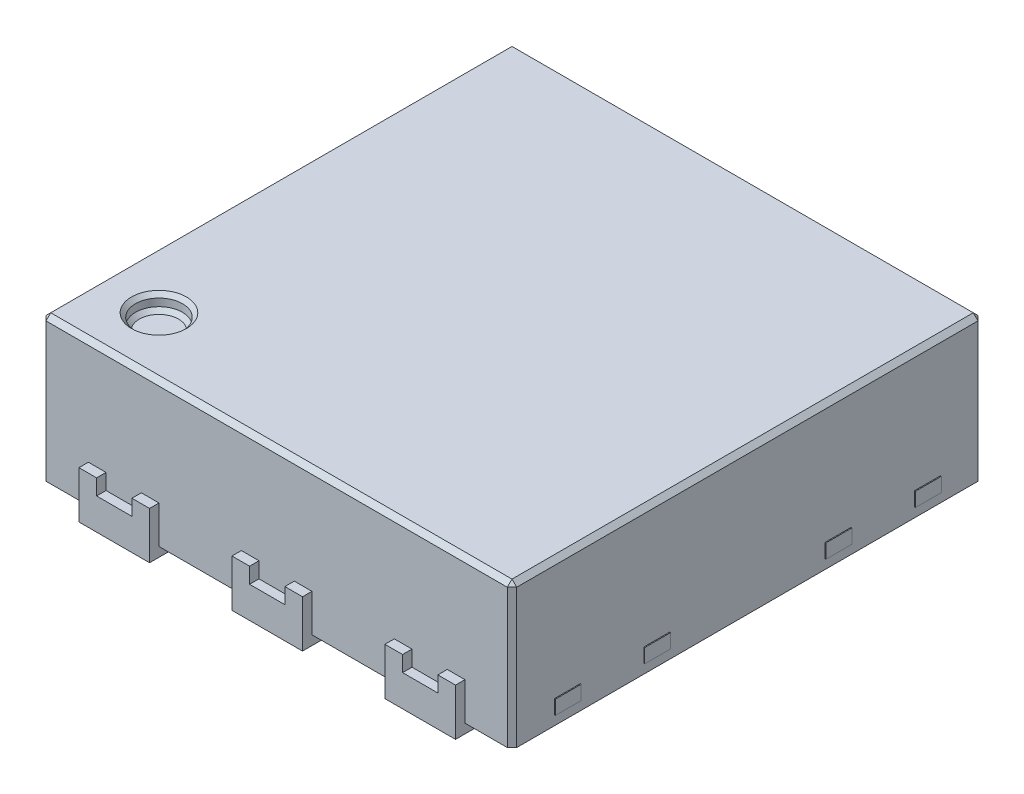
SolidWorks part; units mm, degrees
ref_plane "Front Plane" through (0, 0, 0) normal (0, 0, 1) x (1, 0, 0)
ref_plane "Top Plane" through (0, 0, 0) normal (0, 1, 0) x (1, 0, 0)
ref_plane "Right Plane" through (0, 0, 0) normal (1, 0, 0) x (0, 0, -1)
sketch "Sketch1" plane through (0, 0, 0) normal (0, 1, 0) x (1, 0, 0)
  line L0 (0, 0) -> (-0.49, 0) construction
  line L1 (0, 0) -> (0.49, 0) construction
  line L2 (0, 0) -> (0, 0.895) construction
  line L3 (-0.825, 0.5) -> (-0.155, 0.5)
  line L4 (-0.825, -0.5) -> (-0.825, -0.3325) construction
  line L6 (-0.155, 0.5) -> (-0.155, -0.5)
  line L7 (-0.825, 0.5) -> (-0.155, -0.5) construction
  line L8 (-0.825, -0.5) -> (-0.155, 0.5) construction
  line L9 (0.155, 0.5) -> (0.825, 0.5)
  line L10 (0.155, 0.5) -> (0.155, -0.5)
  line L11 (0.155, -0.5) -> (0.825, -0.5)
  line L12 (0.825, 0.5) -> (0.825, -0.5)
  line L13 (0.155, 0.5) -> (0.825, -0.5) construction
  line L14 (0.155, -0.5) -> (0.825, 0.5) construction
  line L15 (0, 0.895) -> (0.65, 0.895) construction
  line L16 (-0.15, 1.04) -> (0.15, 1.04)
  line L17 (-0.15, 1.04) -> (-0.15, 0.75)
  line L18 (-0.15, 0.75) -> (0.15, 0.75)
  line L19 (0.15, 1.04) -> (0.15, 0.75)
  line L20 (-0.15, 1.04) -> (0.15, 0.75) construction
  line L21 (-0.15, 0.75) -> (0.15, 1.04) construction
  line L22 (0, 0.895) -> (-0.65, 0.895) construction
  line L23 (0, 0) -> (0, -0.895) construction
  line L24 (-0.8, 1.04) -> (-0.5, 1.04)
  line L25 (-0.8, 1.04) -> (-0.8, 0.75)
  line L26 (-0.8, 0.75) -> (-0.5, 0.75)
  line L27 (-0.5, 1.04) -> (-0.5, 0.75)
  line L28 (-0.8, 1.04) -> (-0.5, 0.75) construction
  line L29 (-0.8, 0.75) -> (-0.5, 1.04) construction
  line L30 (0.5, 1.04) -> (0.8, 1.04)
  line L31 (0.5, 1.04) -> (0.5, 0.75)
  line L32 (0.5, 0.75) -> (0.8, 0.75)
  line L33 (0.8, 1.04) -> (0.8, 0.75)
  line L34 (0.5, 1.04) -> (0.8, 0.75) construction
  line L35 (0.5, 0.75) -> (0.8, 1.04) construction
  line L36 (0, -0.895) -> (0.65, -0.895) construction
  line L37 (-0.15, -0.75) -> (0.15, -0.75)
  line L38 (-0.15, -0.75) -> (-0.15, -1.04)
  line L39 (-0.15, -1.04) -> (0.15, -1.04)
  line L40 (0.15, -0.75) -> (0.15, -1.04)
  line L41 (-0.15, -0.75) -> (0.15, -1.04) construction
  line L42 (-0.15, -1.04) -> (0.15, -0.75) construction
  line L43 (0, -0.895) -> (-0.65, -0.895) construction
  line L44 (-0.155, -0.5) -> (-0.6575, -0.5)
  line L45 (0.5, -0.75) -> (0.8, -0.75)
  line L46 (0.5, -0.75) -> (0.5, -1.04)
  line L47 (0.5, -1.04) -> (0.8, -1.04)
  line L48 (0.8, -0.75) -> (0.8, -1.04)
  line L49 (0.5, -0.75) -> (0.8, -1.04) construction
  line L50 (0.5, -1.04) -> (0.8, -0.75) construction
  line L51 (-0.5, -0.75) -> (-0.8, -0.75)
  line L52 (-0.5, -0.75) -> (-0.5, -1.04)
  line L53 (-0.5, -1.04) -> (-0.8, -1.04)
  line L54 (-0.8, -0.75) -> (-0.8, -1.04)
  line L55 (-0.5, -0.75) -> (-0.8, -1.04) construction
  line L56 (-0.5, -1.04) -> (-0.8, -0.75) construction
  line L57 (-0.6575, -0.5) -> (-0.825, -0.3325)
  line L58 (-0.825, -0.3325) -> (-0.825, 0.5)
  line L59 (-0.825, -0.5) -> (-0.6575, -0.5) construction
  dimension "Pitch_BigPads" = 0.49
  dimension "D2" = 0.29
  dimension "D3" = 0.895
  dimension "D4" = 0.3
  dimension "D5" = 0.65
  dimension "D6" = 1
  dimension "D1" = 0.67
  dimension "D7" = 0.1675
extrude "Boss-Extrude1" add sketch "Sketch1" along normal blind 0.2
sketch "Sketch2" plane through (0, 0, 1.04) normal (0, 0, 1) x (1, 0, 0)
  line L0 (-0.8, 0.2) -> (-0.5, 0.2) construction
  line L1 (-0.725, 0.2667) -> (-0.575, 0.2667)
  line L2 (-0.725, 0.2667) -> (-0.725, 0.1333)
  line L3 (-0.725, 0.1333) -> (-0.575, 0.1333)
  line L4 (-0.575, 0.2667) -> (-0.575, 0.1333)
  line L5 (-0.725, 0.2667) -> (-0.575, 0.1333) construction
  line L6 (-0.725, 0.1333) -> (-0.575, 0.2667) construction
  line L7 (-0.15, 0.2) -> (0.15, 0.2) construction
  line L8 (-0.075, 0.2667) -> (0.075, 0.2667)
  line L9 (-0.075, 0.2667) -> (-0.075, 0.1333)
  line L10 (-0.075, 0.1333) -> (0.075, 0.1333)
  line L11 (0.075, 0.2667) -> (0.075, 0.1333)
  line L12 (-0.075, 0.2667) -> (0.075, 0.1333) construction
  line L13 (-0.075, 0.1333) -> (0.075, 0.2667) construction
  line L14 (0.5, 0.2) -> (0.8, 0.2) construction
  line L15 (0.575, 0.2667) -> (0.725, 0.2667)
  line L16 (0.575, 0.2667) -> (0.575, 0.1333)
  line L17 (0.575, 0.1333) -> (0.725, 0.1333)
  line L18 (0.725, 0.2667) -> (0.725, 0.1333)
  line L19 (0.575, 0.2667) -> (0.725, 0.1333) construction
  line L20 (0.575, 0.1333) -> (0.725, 0.2667) construction
  point P0 (-0.65, 0.2)
  point P7 (0, 0.2)
  point P14 (0.65, 0.2)
  dimension "D1" = 0.15
  dimension "D2" = 0.1333
extrude "Cut-Extrude1" cut sketch "Sketch2" against normal through all
sketch "Sketch3" plane through (0, 0, 0) normal (0, 1, 0) x (1, 0, 0)
  line L1 (-1, 1) -> (1, 1)
  line L2 (-1, 1) -> (-1, -1)
  line L3 (-1, -1) -> (1, -1)
  line L4 (1, 1) -> (1, -1)
  line L5 (-1, 1) -> (1, -1) construction
  line L6 (-1, -1) -> (1, 1) construction
  point P0 (0, 0)
  dimension "D1" = 2
  dimension "D2" = 2
extrude "Boss-Extrude2" add sketch "Sketch3" along direction (0, 1, 0) on the side of the normal blind 0.61 from offset 0.04 separate body
sketch "Sketch4" plane through (1, 0, 0) normal (1, 0, 0) x (0, 0, -1)
  line L0 (0, 0) -> (0, 0.11) construction
  line L1 (0, 0.11) -> (-0.385, 0.11) construction
  line L2 (0, 0.11) -> (0.385, 0.11) construction
  line L3 (0, 0.11) -> (0.765, 0.11) construction
  line L4 (0, 0.11) -> (-0.765, 0.11) construction
  line L6 (-0.82, 0.14) -> (-0.71, 0.14)
  line L7 (-0.82, 0.14) -> (-0.82, 0.08)
  line L8 (-0.82, 0.08) -> (-0.71, 0.08)
  line L9 (-0.71, 0.14) -> (-0.71, 0.08)
  line L10 (-0.82, 0.14) -> (-0.71, 0.08) construction
  line L11 (-0.82, 0.08) -> (-0.71, 0.14) construction
  line L12 (-0.44, 0.14) -> (-0.33, 0.14)
  line L13 (-0.44, 0.14) -> (-0.44, 0.08)
  line L14 (-0.44, 0.08) -> (-0.33, 0.08)
  line L15 (-0.33, 0.14) -> (-0.33, 0.08)
  line L16 (-0.44, 0.14) -> (-0.33, 0.08) construction
  line L17 (-0.44, 0.08) -> (-0.33, 0.14) construction
  line L18 (0.33, 0.14) -> (0.44, 0.14)
  line L19 (0.33, 0.14) -> (0.33, 0.08)
  line L20 (0.33, 0.08) -> (0.44, 0.08)
  line L21 (0.44, 0.14) -> (0.44, 0.08)
  line L22 (0.33, 0.14) -> (0.44, 0.08) construction
  line L23 (0.33, 0.08) -> (0.44, 0.14) construction
  line L24 (0.71, 0.14) -> (0.82, 0.14)
  line L25 (0.71, 0.14) -> (0.71, 0.08)
  line L26 (0.71, 0.08) -> (0.82, 0.08)
  line L27 (0.82, 0.14) -> (0.82, 0.08)
  line L28 (0.71, 0.14) -> (0.82, 0.08) construction
  line L29 (0.71, 0.08) -> (0.82, 0.14) construction
  dimension "D1" = 0.11
  dimension "D2" = 0.765
  dimension "D3" = 0.385
  dimension "D4" = 0.11
extrude "Boss-Extrude3" add sketch "Sketch4" along normal blind 0.004 and the other way blind 2.004 separate body
sketch "Sketch5" plane through (0, 0.65, 0) normal (0, 1, 0) x (1, 0, 0)
  line L0 (-1, -1) -> (-0.75, -1) construction
  line L1 (-1, -1) -> (1, -1) construction
  line L2 (-0.75, -1) -> (-0.75, -0.75) construction
  circle A0 centre (-0.75, -0.75) radius 0.1
  dimension "D1" = 0.25
extrude "Cut-Extrude2" cut sketch "Sketch5" against normal blind 0.065
chamfer "Chamfer1" distance 0.0167 angle 45 2 edges at (-0.75, 0.65, 0.85) (-0.75, 0.585, 0.85)
chamfer "Chamfer2" distance 0.02 angle 45 8 edges at (-1, 0.345, -1) (1, 0.345, -1) (1, 0.345, 1) (-1, 0.345, 1) (-1, 0.65, 0) (0, 0.65, 1) (1, 0.65, 0) (0, 0.65, -1)
equation "\"A\"= 0.65"
equation "\"A1\"=0.04"
equation "\"bp\"= 0.3"
equation "\"D\"= 2"
equation "\"D1\"= 0.67"
equation "\"E\"= 2"
equation "\"E1\"= 1"
equation "\"Pitch_SmallPads\"= 0.65"
equation "\"Pitch_BigPads\"= 0.49"
equation "\"Lp\"= 0.25"
equation "\"v\"= 0.1"
equation "\"y\"= 0.05"
equation "\"y1\"= 0.05"
equation "\"D2@Sketch1\"=\"Lp\"+\"A1\""
equation "\"D3@Sketch1\"=(\"E\"-\"Lp\"+\"A1\")/2"
equation "\"D4@Sketch1\"=\"bp\""
equation "\"D5@Sketch1\"=\"Pitch_SmallPads\""
equation "\"D6@Sketch1\"=\"E1\""
equation "\"D1@Sketch1\"=\"D1\""
equation "\"NR1Corner\"= \"D1\" / 4"
equation "\"D7@Sketch1\"=\"NR1Corner\""
equation "\"D1@Sketch3\" = \"D\""
equation "\"D2@Sketch3\" = \"E\""
equation "\"D1@Boss-Extrude2\"=\"A\"-\"A1\""
equation "\"D19@Boss-Extrude2\"=\"A1\""
equation "\"D1@Sketch2\" = \"bp\" / 2"
equation "\"PinHeigth\"= 0.2"
equation "\"D1@Boss-Extrude1\"=\"PinHeigth\""
equation "\"D2@Sketch2\" = \"PinHeigth\" * 2 / 3"
equation "\"D1@Boss-Extrude3\"=(\"A1\"/10)"
equation "\"D2@Boss-Extrude3\"=\"D\"+(\"A1\"/10)"
equation "\"D1@Sketch5\"=\"D\"/8"
equation "\"D2@Sketch5\"=\"D\"/10"
equation "\"D1@Chamfer1\"=\"D\"/120"
equation "\"D1@Chamfer2\"=\"D\"/100"
equation "\"D1@Cut-Extrude2\"=\"A\"/10"
equation "\"D1@Sketch4\"=\"A1\"*2.75"
equation "\"D4@Sketch4\"=\"A1\"*2.75"
equation "\"D3@Sketch4\"=\"E\"*0.1925"
equation "\"D2@Sketch4\"=\"D\"*0.3825"
